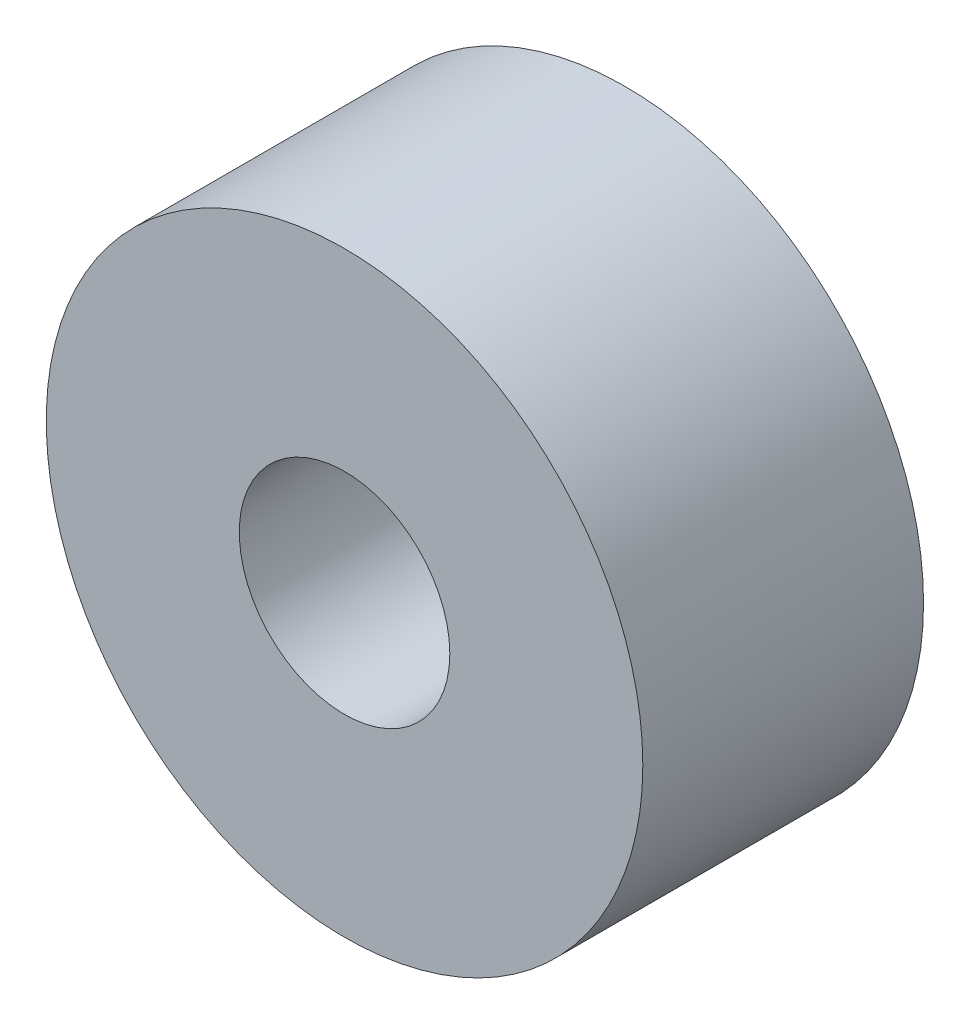
SolidWorks part; units mm, degrees
ref_plane "前视基准面" through (0, 0, 0) normal (0, 0, 1) x (1, 0, 0)
ref_plane "上视基准面" through (0, 0, 0) normal (0, 1, 0) x (1, 0, 0)
ref_plane "右视基准面" through (0, 0, 0) normal (1, 0, 0) x (0, 0, -1)
other "Configuration Table"
sketch "草图1" plane through (0, 0, 0) normal (1, 0, 0) x (0, 0, -1)
  line L0 (34, 0) -> (60, 0) construction
  line L1 (39, 6) -> (39, 17)
  line L2 (39, 17) -> (55, 17)
  line L3 (55, 17) -> (55, 6)
  line L4 (55, 6) -> (39, 6)
revolve "旋转1" add sketch "草图1" angle 360 about L0
